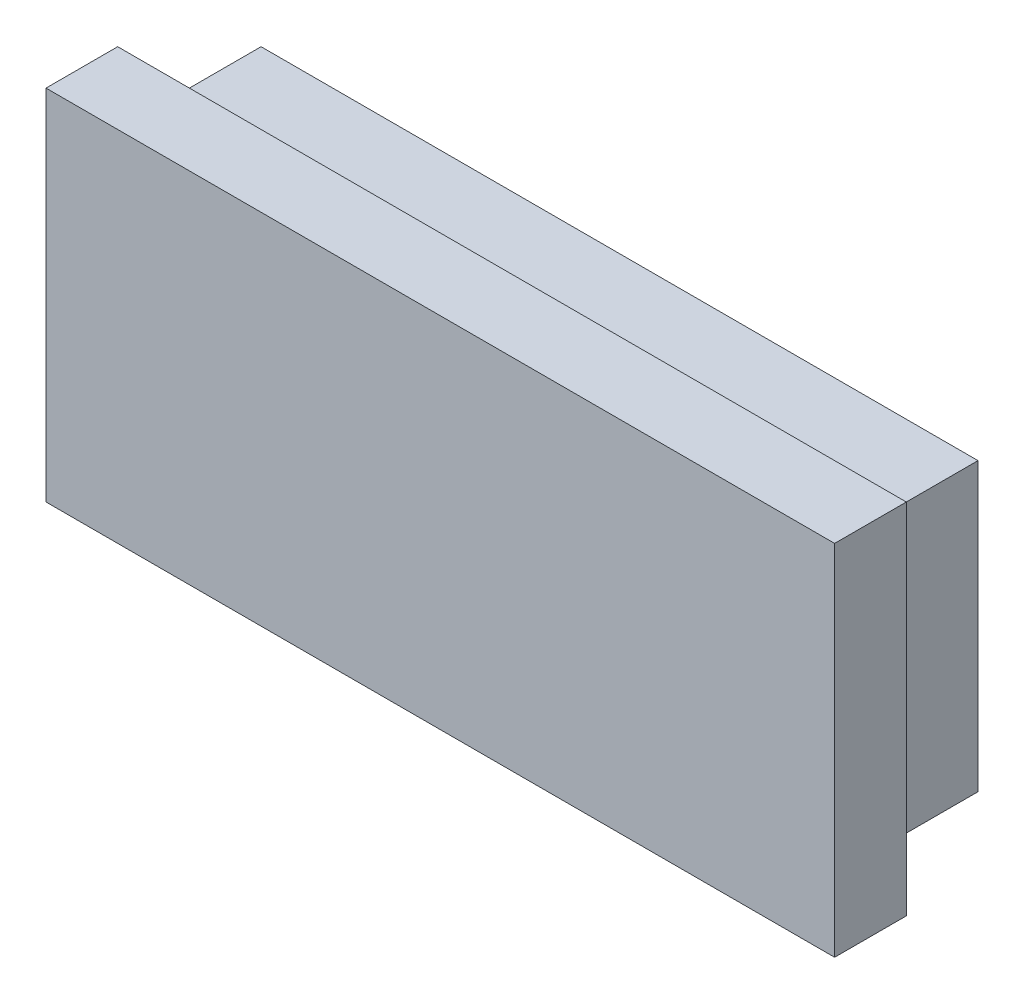
SolidWorks part; units mm, degrees
ref_plane "Front Plane" through (0, 0, 0) normal (0, 0, 1) x (1, 0, 0)
ref_plane "Top Plane" through (0, 0, 0) normal (0, 1, 0) x (1, 0, 0)
ref_plane "Right Plane" through (0, 0, 0) normal (1, 0, 0) x (0, 0, -1)
sketch "Sketch1" plane through (0, 0, 0) normal (0, 0, 1) x (1, 0, 0)
  line L1 (-6.35, 2.54) -> (6.35, 2.54)
  line L2 (-6.35, 2.54) -> (-6.35, -2.54)
  line L3 (-6.35, -2.54) -> (6.35, -2.54)
  line L4 (6.35, 2.54) -> (6.35, -2.54)
  line L5 (-6.35, 2.54) -> (6.35, -2.54) construction
  line L6 (-6.35, -2.54) -> (6.35, 2.54) construction
  point P0 (0, 0)
  dimension "D1" = 5.08
  dimension "D2" = 12.7
extrude "Boss-Extrude1" add sketch "Sketch1" along normal mid plane 2.54 contours L1 L4 L3 L2
sketch "Sketch2" plane through (0, 0, 1.27) normal (0, 0, 1) x (1, 0, 0)
  line L1 (-6.985, 3.175) -> (6.985, 3.175)
  line L2 (-6.985, 3.175) -> (-6.985, -3.175)
  line L3 (-6.985, -3.175) -> (6.985, -3.175)
  line L4 (6.985, 3.175) -> (6.985, -3.175)
  line L5 (-6.985, 3.175) -> (6.985, -3.175) construction
  line L6 (-6.985, -3.175) -> (6.985, 3.175) construction
  point P0 (0, 0)
  dimension "D1" = 6.35
  dimension "D2" = 13.97
extrude "Boss-Extrude2" add sketch "Sketch2" along normal mid plane 1.27
